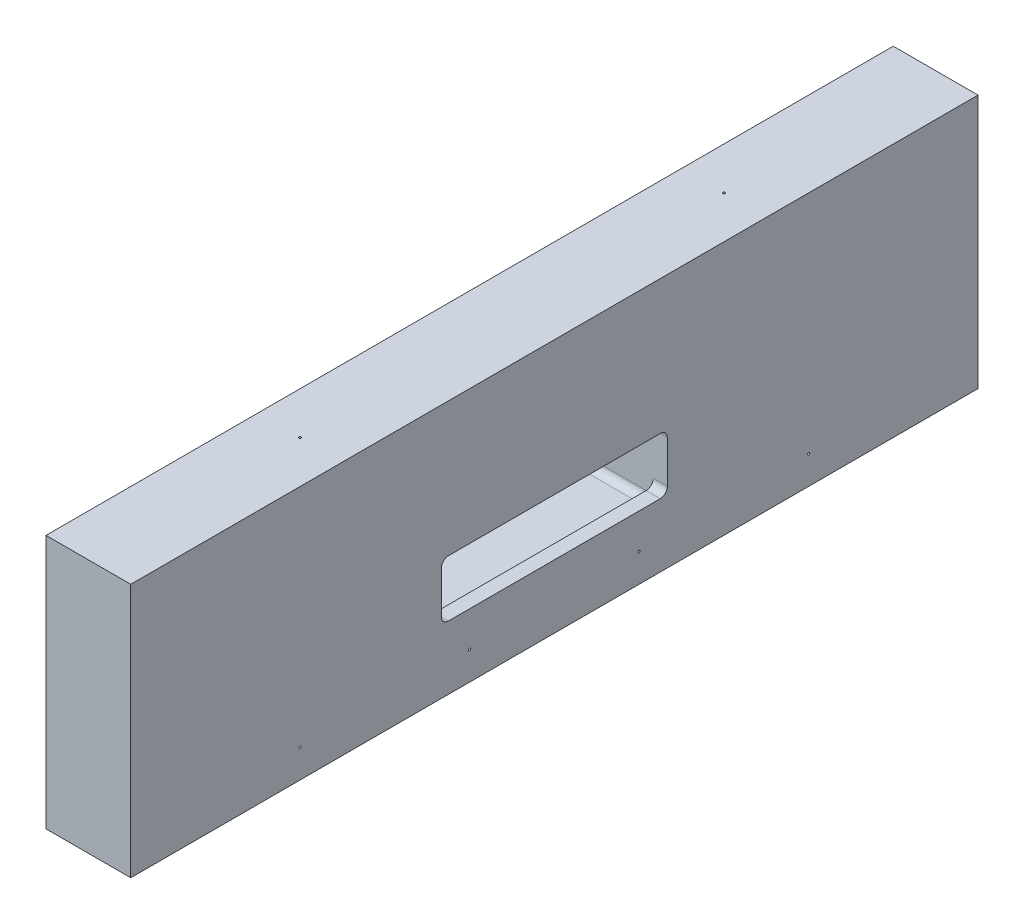
SolidWorks part; units mm, degrees
material "Maple"
ref_plane "Front Plane" through (0, 0, 0) normal (0, 0, 1) x (1, 0, 0)
ref_plane "Top Plane" through (0, 0, 0) normal (0, 1, 0) x (1, 0, 0)
ref_plane "Right Plane" through (0, 0, 0) normal (1, 0, 0) x (0, 0, -1)
sketch "Sketch1" plane through (0, 0, 0) normal (1, 0, 0) x (0, 0, -1)
  line L1 (0, 0) -> (762, 0)
  line L2 (0, 0) -> (0, 228.6)
  line L3 (0, 228.6) -> (762, 228.6)
  line L4 (762, 0) -> (762, 228.6)
  dimension "D1" = 762
  dimension "D2" = 228.6
extrude "Boss-Extrude1" add sketch "Sketch1" along normal blind 76.2
sketch "Sketch2" plane through (0, 0, 0) normal (-1, 0, 0) x (0, 0, 1)
  line L1 (-482.6, 44.45) -> (-279.4, 44.45)
  line L2 (-482.6, 44.45) -> (-482.6, 139.7)
  line L3 (-482.6, 139.7) -> (-279.4, 139.7)
  line L4 (-279.4, 44.45) -> (-279.4, 139.7)
  line L6 (0, 0) -> (-762, 0) construction
  line L7 (-762, 0) -> (-762, 228.6) construction
  point P6 (-381, 139.7)
  dimension "D1" = 44.45
  dimension "D2" = 381
  dimension "D3" = 95.25
  dimension "D4" = 203.2
extrude "Cut-Extrude1" cut sketch "Sketch2" against normal blind 63.5
sketch "Sketch3" plane through (63.5, 0, 0) normal (-1, 0, 0) x (0, 0, 1)
  line L0 (-279.4, 44.45) -> (-279.4, 139.7) construction
  line L1 (-482.6, 107.95) -> (-279.4, 107.95)
  line L2 (-482.6, 107.95) -> (-482.6, 57.15)
  line L3 (-482.6, 57.15) -> (-279.4, 57.15)
  line L4 (-279.4, 107.95) -> (-279.4, 57.15)
  line L5 (-482.6, 44.45) -> (-279.4, 44.45) construction
  line L6 (-482.6, 139.7) -> (-482.6, 44.45) construction
  dimension "D1" = 12.7
  dimension "D2" = 50.8
extrude "Cut-Extrude2" cut sketch "Sketch3" against normal through all
fillet "Fillet1" radius 25.4 2 edges at (31.75, 139.7, -279.4) (31.75, 139.7, -482.6)
sketch "Sketch4" plane through (0, 0, 0) normal (-1, 0, 0) x (0, 0, 1)
  line L1 (-762, 0) -> (-762, 228.6) construction
  line L2 (0, 0) -> (-762, 0) construction
  circle A0 centre (-609.6, 25.4) radius 1.016
  dimension "D3" = 2.032
  dimension "D1" = 152.4
  dimension "D2" = 25.4
extrude "Cut-Extrude3" cut sketch "Sketch4" against normal through all
pattern_linear "LPattern1" count 4 spacing 152.4 along (0, 0, 1) of "Cut-Extrude3"
fillet "Fillet2" radius 6.35 4 edges at (69.85, 57.15, -482.6) (69.85, 107.95, -482.6) (69.85, 57.15, -279.4) (69.85, 107.95, -279.4)
fillet "Fillet3" radius 6.35 2 edges at (31.75, 44.45, -279.4) (31.75, 44.45, -482.6)
sketch "Sketch6" plane through (0, 228.6, 0) normal (0, 1, 0) x (1, 0, 0)
  line L0 (38.1, 1524) -> (38.1, 0) construction
  line L2 (76.2, 0) -> (0, 0) construction
  circle A0 centre (38.1, 571.5) radius 1.016
  circle A1 centre (38.1, 190.5) radius 1.016
  point P0 (38.1, 571.5)
  point P3 (38.1, 762)
  point P4 (38.1, 190.5)
  dimension "D3" = 2.032
  dimension "D4" = 2.032
  dimension "D1" = 381
  dimension "D2" = 190.5
extrude "Cut-Extrude4" cut sketch "Sketch6" against normal blind 50.8
